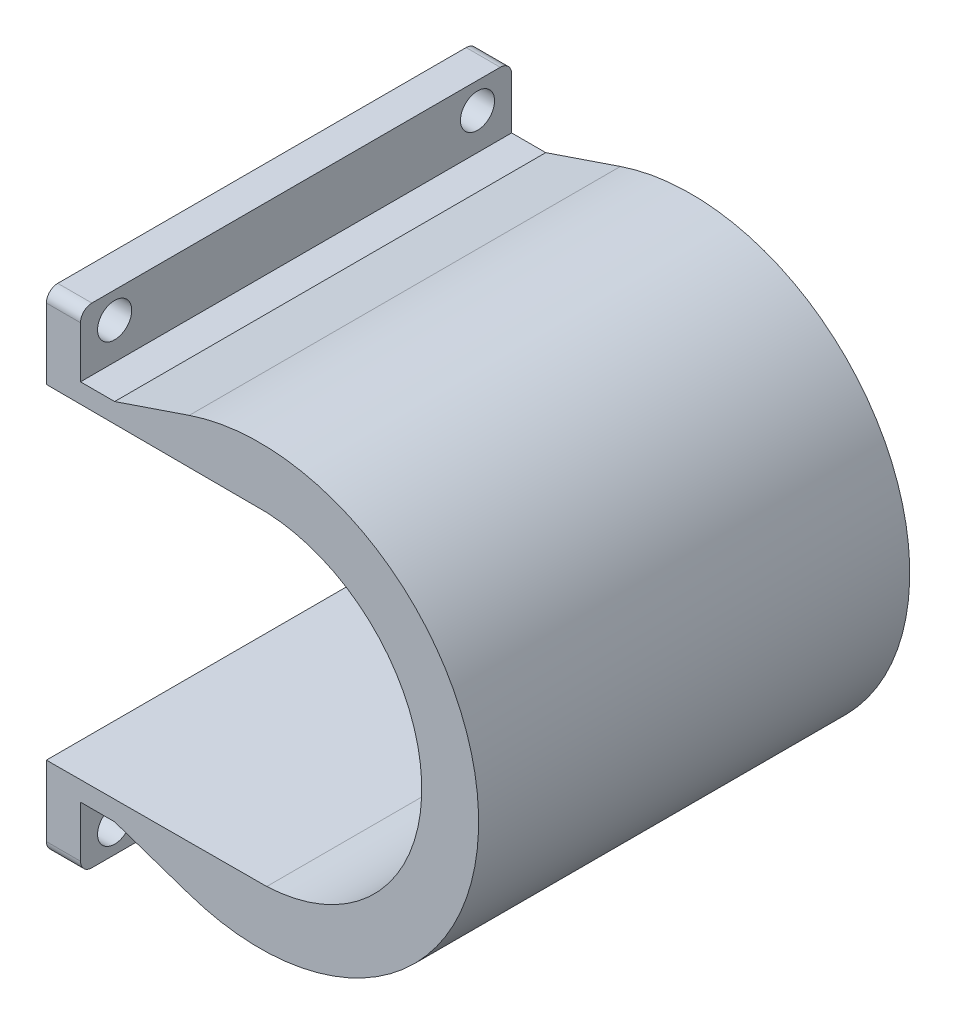
SolidWorks part; units mm, degrees
ref_plane "前视基准面" through (0, 0, 0) normal (0, 0, 1) x (1, 0, 0)
ref_plane "上视基准面" through (0, 0, 0) normal (0, 1, 0) x (1, 0, 0)
ref_plane "右视基准面" through (0, 0, 0) normal (1, 0, 0) x (0, 0, -1)
other "Configuration Table"
sketch "草图1" plane through (0, 0, 0) normal (0, 0, 1) x (1, 0, 0)
  line L0 (0, 0) -> (0, -7.2)
  line L1 (0, -7.2) -> (19.3716, -7.2636)
  line L6 (0, 0) -> (3, 0)
  line L7 (3, 0) -> (3, -5.5)
  line L12 (50.8058, -21.5) -> (38, -21.5) construction
  line L14 (0, -35.8) -> (19.3716, -35.7364)
  line L15 (0, -43) -> (0, -35.8)
  line L16 (3, -43) -> (3, -37.5)
  line L17 (0, -43) -> (3, -43)
  line L18 (3, -5.5) -> (6, -5.5)
  line L19 (6, -5.5) -> (12.5603, -3.2723)
  line L20 (6, -37.5) -> (12.5603, -39.7277)
  line L21 (3, -37.5) -> (6, -37.5)
  arc A1 (19.3716, -7.2636) -> (19.3716, -35.7364) centre (18.75, -21.5) cw
  arc A2 (12.5603, -39.7277) -> (12.5603, -3.2723) centre (18.75, -21.5) ccw
  dimension "D1" = 5.5
  dimension "D2" = 14.25
  dimension "D3" = 32
  dimension "D8" = 19.25
  dimension "D4" = 28.6
  dimension "D5" = 3
  dimension "D6" = 175
  dimension "D7" = 35
  dimension "D9" = 3
extrude "凸台-拉伸1" add sketch "草图1" along normal blind 37.9
sketch "草图2" plane through (0, 0, 0) normal (-1, 0, 0) x (0, 0, 1)
  line L0 (37.9, 0) -> (0, 0) construction
  line L1 (0, 0) -> (0, -7.2) construction
  line L2 (18.95, 0) -> (18.95, -2.8287) construction
  line L3 (37.9, -21.5) -> (34.9, -21.5) construction
  line L4 (37.9, -35.7364) -> (37.9, -7.2636) construction
  circle A0 centre (3, -2.3) radius 1.5
  circle A1 centre (34.9, -2.3) radius 1.5
  circle A2 centre (3, -40.7) radius 1.5
  circle A3 centre (34.9, -40.7) radius 1.5
  dimension "D1" = 3
  dimension "D2" = 2.3
  dimension "D3" = 3
extrude "切除-拉伸1" cut sketch "草图2" against normal up to next
fillet "圆角1" radius 1 4 edges at (1.5, -43, 0) (1.5, -43, 37.9) (1.5, 0, 37.9) (1.5, 0, 0)
